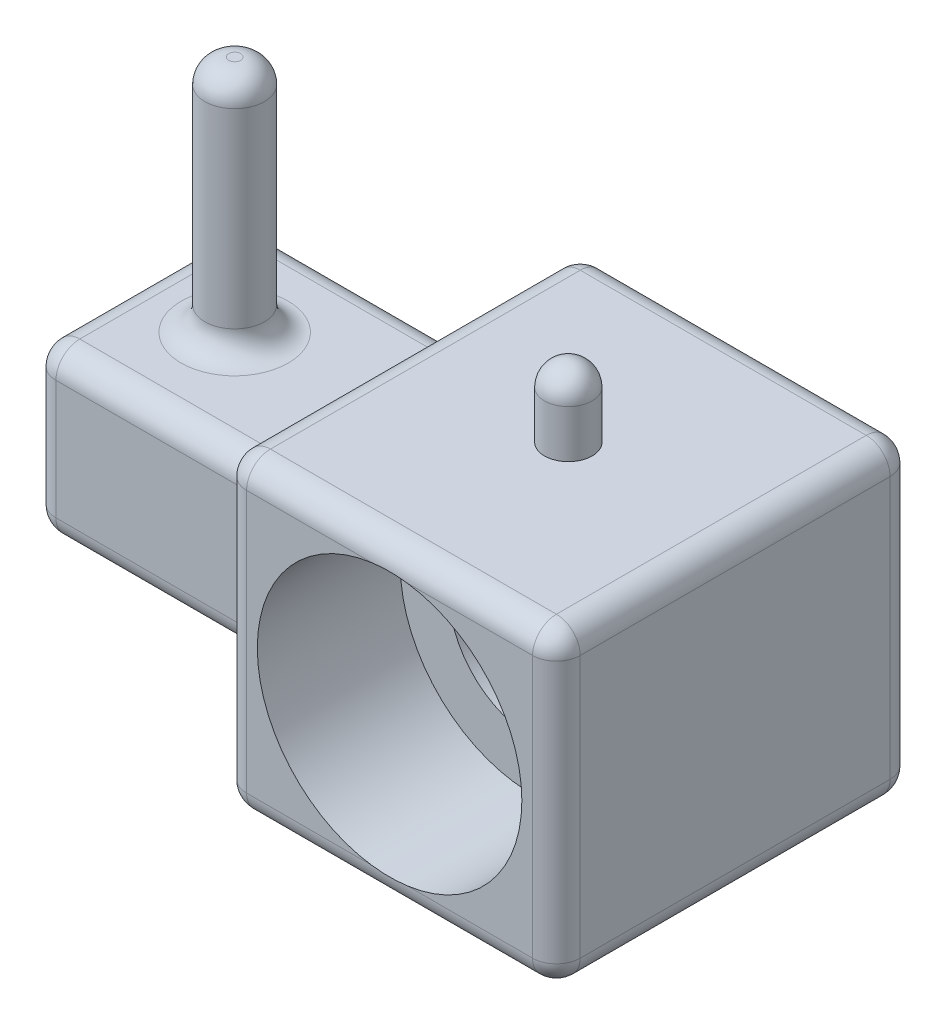
SolidWorks part; units mm, degrees
ref_plane "Alzado" through (0, 0, 0) normal (0, 0, 1) x (1, 0, 0)
ref_plane "Planta" through (0, 0, 0) normal (0, 1, 0) x (1, 0, 0)
ref_plane "Vista lateral" through (0, 0, 0) normal (1, 0, 0) x (0, 0, -1)
sketch "Croquis1" plane through (0, 0, 0) normal (0, 0, 1) x (1, 0, 0)
  line L1 (-7, 6.5) -> (7, 6.5)
  line L2 (-7, 6.5) -> (-7, -6.5)
  line L3 (-7, -6.5) -> (7, -6.5)
  line L4 (7, 6.5) -> (7, -6.5)
  circle A0 centre (0, 0) radius 5.75 construction
  circle A1 centre (0, 0) radius 3.5
  point P7 (0, 6.5)
  point P8 (-7, 0)
  dimension "D1" = 11.5
  dimension "D3" = 7
  dimension "D2" = 13
  dimension "D4" = 14
extrude "Saliente-Extruir1" add sketch "Croquis1" against normal blind 15
sketch "Croquis2" plane through (0, 0, 0) normal (0, 0, -1) x (-1, 0, 0)
  circle A0 centre (0, 0) radius 5.55
  dimension "D1" = 11.1
sketch "Croquis3" plane through (0, 6.5, 0) normal (0, 1, 0) x (1, 0, 0)
  line L1 (7, 15) -> (7, 0) construction
  circle A0 centre (0, 7.5) radius 1
  point P8 (7, 7.5)
  dimension "D1" = 2
extrude "Saliente-Extruir2" add sketch "Croquis3" along normal blind 3
fillet "Redondeo2" radius 1 1 edges at (-1, 9.5, -7.5)
sketch "Croquis4" plane through (0, -6.5, 0) normal (0, -1, 0) x (1, 0, 0)
  line L1 (-7, -15) -> (-7, 0) construction
  circle A0 centre (0, -7.5) radius 1
  point P7 (-7, -7.5)
  dimension "D1" = 2
extrude "Saliente-Extruir3" add sketch "Croquis4" along normal blind 3
fillet "Redondeo3" radius 1 2 edges at (0, -6.5, -8.5) (0, -9.5, -8.5)
fillet "Redondeo4" radius 1 12 edges at (7, -6.5, -7.5) (0, 6.5, 0) (7, 0, 0) (0, -6.5, 0) (-7, 0, 0) (-7, 6.5, -7.5) (-7, -6.5, -7.5) (-7, 0, -15) (0, -6.5, -15) (0, 6.5, -15) (7, 6.5, -7.5) (7, 0, -15)
sketch "Croquis5" plane through (-7, 0, 0) normal (-1, 0, 0) x (0, 0, 1)
  line L1 (-12, 3.5) -> (-3, 3.5)
  line L2 (-12, 3.5) -> (-12, -3.5)
  line L3 (-12, -3.5) -> (-3, -3.5)
  line L4 (-3, 3.5) -> (-3, -3.5)
  line L5 (-1, 5.5) -> (-14, 5.5) construction
  line L6 (-14, 5.5) -> (-14, -5.5) construction
  point P4 (-3, 0)
  point P8 (-7.5, 5.5)
  point P9 (-7.5, 3.5)
  dimension "D1" = 2
  dimension "D2" = 2
extrude "Saliente-Extruir4" add sketch "Croquis5" along normal blind 11
fillet "Redondeo5" radius 1 12 edges at (-7, -3.5, -7.5) (-12.5, -3.5, -3) (-7, 0, -3) (-18, 0, -3) (-18, -3.5, -7.5) (-12.5, 3.5, -3) (-18, 3.5, -7.5) (-7, 3.5, -7.5) (-12.5, 3.5, -12) (-18, 0, -12) (-12.5, -3.5, -12) (-7, 0, -12)
sketch "Croquis6" plane through (0, 3.5, 0) normal (0, 1, 0) x (1, 0, 0)
  line L5 (-8, 4) -> (-8, 11) construction
  line L7 (-17, 11) -> (-17, 4) construction
  circle A0 centre (-14, 7.5) radius 1.2484
  point P6 (-8, 7.5)
  dimension "D1" = 2.4968
  dimension "D2" = 3
extrude "Saliente-Extruir5" add sketch "Croquis6" along normal blind 10
fillet "Redondeo6" radius 1 2 edges at (-12.7516, 3.5, -7.5) (-15.2484, 13.5, -7.5)
extrude "Cortar-Extruir2" cut sketch "Croquis2" along normal blind 6
